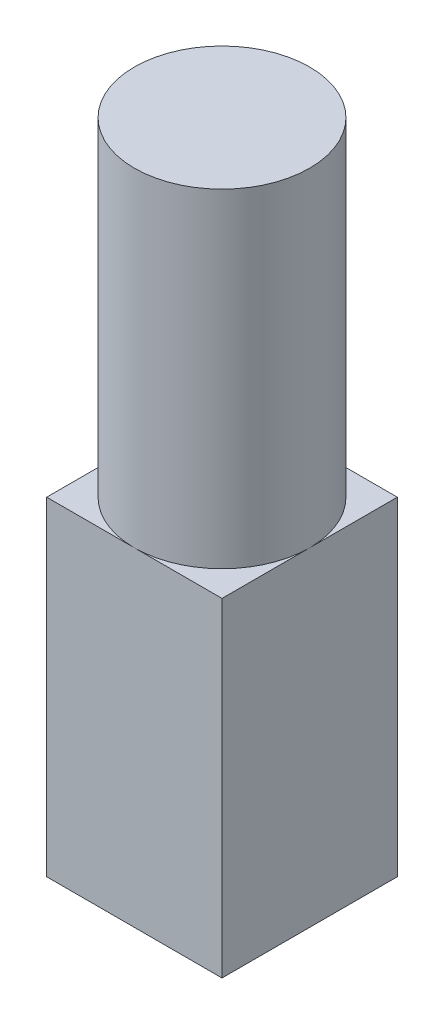
SolidWorks part; units mm, degrees
ref_plane "Front Plane" through (0, 0, 0) normal (0, 0, 1) x (1, 0, 0)
ref_plane "Top Plane" through (0, 0, 0) normal (0, 1, 0) x (1, 0, 0)
ref_plane "Right Plane" through (0, 0, 0) normal (1, 0, 0) x (0, 0, -1)
sketch "Sketch1" plane through (0, 0, 0) normal (0, 1, 0) x (1, 0, 0)
  line L1 (-87.6409, -11.6374) -> (-86.0409, -11.6374)
  line L2 (-87.6409, -11.6374) -> (-87.6409, -13.2374)
  line L3 (-87.6409, -13.2374) -> (-86.0409, -13.2374)
  line L4 (-86.0409, -11.6374) -> (-86.0409, -13.2374)
extrude "Boss-Extrude1" add sketch "Sketch1" along normal blind 3
sketch "Sketch2" plane through (0, 3, 0) normal (0, 1, 0) x (1, 0, 0)
  circle A0 centre (-86.8409, -12.4374) radius 0.8
extrude "Boss-Extrude2" add sketch "Sketch2" along normal blind 3
